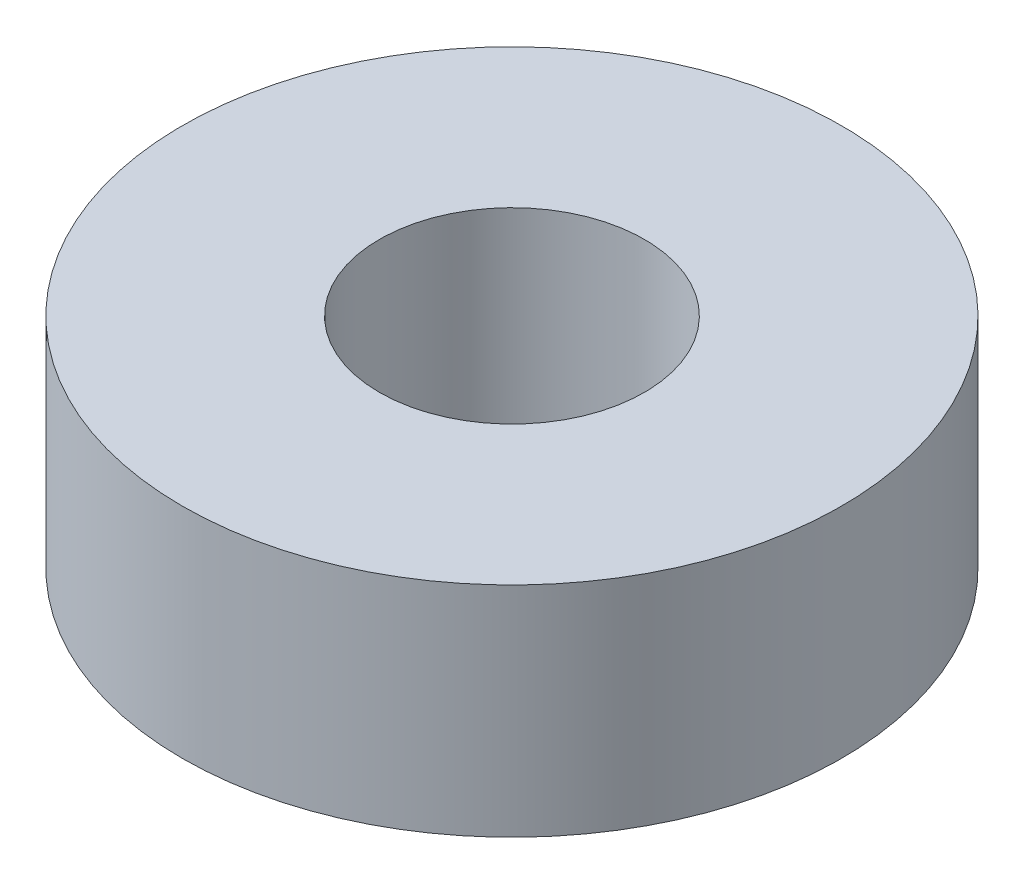
SolidWorks part; units mm, degrees
ref_plane "Front Plane" through (0, 0, 0) normal (0, 0, 1) x (1, 0, 0)
ref_plane "Top Plane" through (0, 0, 0) normal (0, 1, 0) x (1, 0, 0)
ref_plane "Right Plane" through (0, 0, 0) normal (1, 0, 0) x (0, 0, -1)
sketch "Sketch1" plane through (0, 0, 0) normal (0, 1, 0) x (1, 0, 0)
  circle A0 centre (0, 0) radius 3.45
  circle A1 centre (0, 0) radius 9.5
  dimension "D1" = 19
  dimension "D2" = 6.9
extrude "Boss-Extrude1" add sketch "Sketch1" along normal mid plane 6.1
sketch "Sketch2" plane through (0, 3.05, 0) normal (0, 1, 0) x (1, 0, 0)
  circle A0 centre (0, 0) radius 9.2
  circle A1 centre (0, 0) radius 9.5
  circle A2 centre (0, 0) radius 9.5
  dimension "D1" = 0
  dimension "D2" = 0.3
extrude "Cut-Extrude1" cut sketch "Sketch2" against normal through all both and the other way through all
sketch "Sketch3" plane through (0, 3.05, 0) normal (0, 1, 0) x (1, 0, 0)
  circle A0 centre (0, 0) radius 3.45 construction
  circle A1 centre (0, 0) radius 3.45 construction
  circle A2 centre (0, 0) radius 3.7
  dimension "D1" = 0.25
extrude "Cut-Extrude2" cut sketch "Sketch3" against normal through all both and the other way through all
